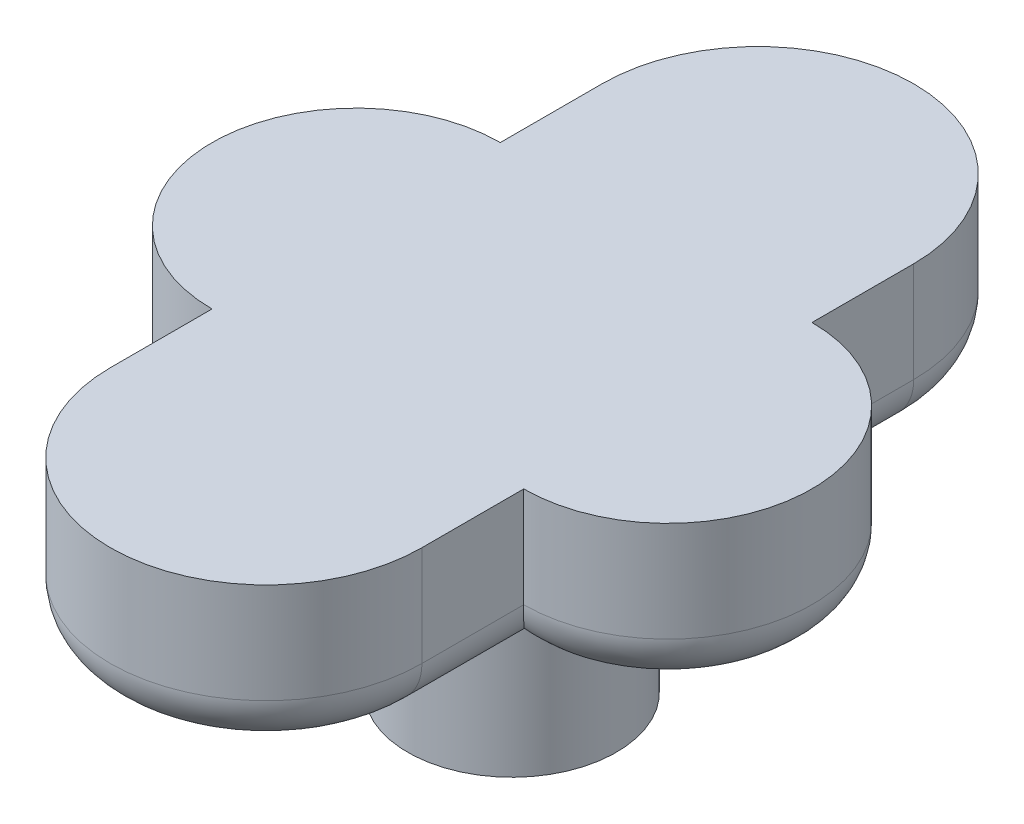
SolidWorks part; units mm, degrees
ref_plane "Alzado" through (0, 0, 0) normal (0, 0, 1) x (1, 0, 0)
ref_plane "Planta" through (0, 0, 0) normal (0, 1, 0) x (1, 0, 0)
ref_plane "Vista lateral" through (0, 0, 0) normal (1, 0, 0) x (0, 0, -1)
sketch "Croquis2" plane through (0, 0, 0) normal (0, 1, 0) x (1, 0, 0)
  line L0 (-56.9942, -9.8133) -> (66.2058, -9.8133) construction
  line L1 (-56.9942, 39.2187) -> (-30.5219, 39.2187) construction
  line L2 (-56.9942, -58.8453) -> (-30.5219, -58.8453) construction
  line L3 (4.6058, -86.7226) -> (4.6058, 67.096) construction
  line L4 (-30.5219, -86.7226) -> (-30.5219, -58.8453) construction
  line L5 (39.7334, -86.7226) -> (39.7334, -58.8453) construction
  line L6 (39.7334, 39.2187) -> (66.2058, 39.2187) construction
  line L7 (-30.5219, 39.2187) -> (-30.5219, 67.096) construction
  line L8 (39.7334, -58.8453) -> (66.2058, -58.8453) construction
  line L9 (39.7334, 39.2187) -> (39.7334, 67.096) construction
  line L10 (-56.9942, -38.5531) -> (-56.9942, 39.2187) construction
  line L13 (-25.9201, -9.8133) -> (-88.0684, -9.8133) construction
  line L18 (35.1316, 18.9265) -> (35.1316, 39.2187)
  line L19 (35.1316, -58.8453) -> (35.1316, -38.5531)
  line L20 (97.2799, -58.8453) -> (97.2799, -38.5531)
  line L21 (97.2799, 18.9265) -> (97.2799, 39.2187)
  arc A0 (-30.5219, -86.7226) -> (39.7334, -86.7226) centre (4.6058, -86.7226) ccw construction
  arc A5 (-56.9942, 39.2187) -> (-56.9942, -58.8453) centre (-56.9942, -9.8133) ccw construction
  arc A6 (66.2058, -58.8453) -> (66.2058, 39.2187) centre (66.2058, -9.8133) ccw construction
  arc A7 (39.7334, 67.096) -> (-30.5219, 67.096) centre (4.6058, 67.096) ccw construction
  arc A12 (35.1316, -38.5531) -> (35.1316, 18.9265) centre (35.1316, -9.8133) cw
  arc A13 (97.2799, -58.8453) -> (35.1316, -58.8453) centre (66.2058, -58.8453) cw
  arc A14 (97.2799, 18.9265) -> (97.2799, -38.5531) centre (97.2799, -9.8133) cw
  arc A15 (35.1316, 39.2187) -> (97.2799, 39.2187) centre (66.2058, 39.2187) cw
  point P2 (4.6058, -9.8133)
  point P3 (4.6058, 11.9637)
  point P9 (4.6058, -9.8133)
  point P11 (-56.9942, -9.8133)
  point P28 (-56.9942, -9.8133)
extrude "Saliente-Extruir1" add sketch "Croquis2" along normal blind 30
sketch "Croquis3" plane through (0, 0, 0) normal (0, -1, 0) x (1, 0, 0)
  circle A1 centre (66.2058, 9.8133) radius 10.8
  circle A3 centre (66.2058, 9.8133) radius 20.8
extrude "Saliente-Extruir2" add sketch "Croquis3" along normal blind 35
fillet "Redondeo1" radius 5 1 edges at (66.2058, 0, -10.9867)
fillet "Redondeo4" radius 10 8 edges at (35.1316, 0, -29.0726) (66.2058, 0, -70.2929) (126.0197, 0, 9.8133) (97.2799, 0, -29.0726) (35.1316, 0, 48.6992) (97.2799, 0, 48.6992) (66.2058, 0, 89.9195) (6.3918, 0, 9.8133)
